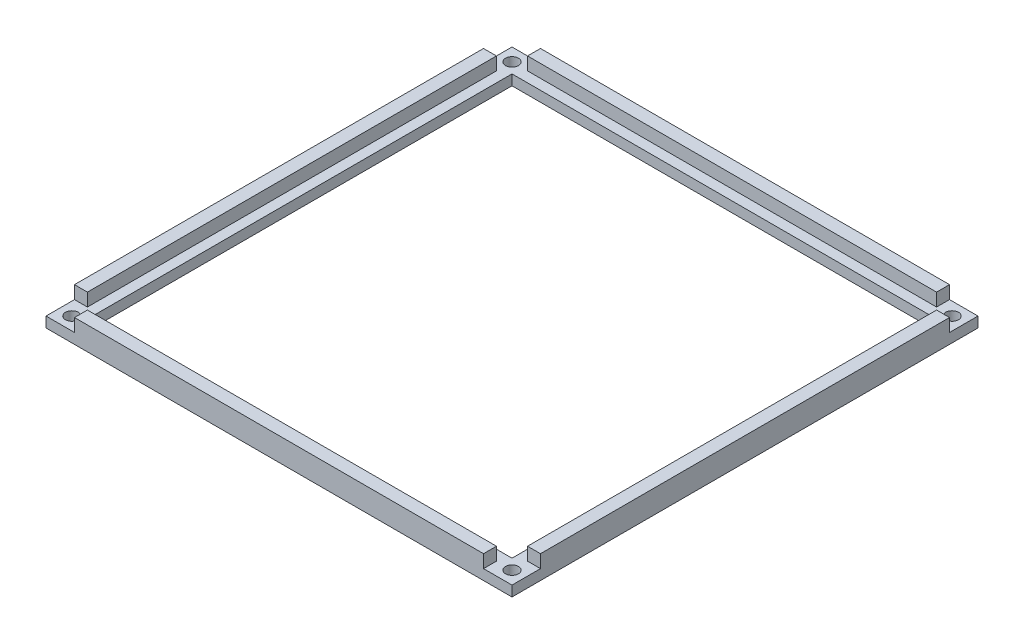
SolidWorks part; units mm, degrees
ref_plane "Alzado" through (0, 0, 0) normal (0, 0, 1) x (1, 0, 0)
ref_plane "Planta" through (0, 0, 0) normal (0, 1, 0) x (1, 0, 0)
ref_plane "Vista lateral" through (0, 0, 0) normal (1, 0, 0) x (0, 0, -1)
sketch "Croquis1" plane through (0, 0, 0) normal (0, 1, 0) x (1, 0, 0)
  line L0 (100, 15) -> (100, 0) construction
  line L1 (0, 0) -> (200, 0)
  line L2 (0, 0) -> (0, 200)
  line L3 (0, 200) -> (200, 200)
  line L4 (200, 0) -> (200, 200)
  line L5 (15, 15) -> (185, 15) construction
  line L6 (15, 15) -> (15, 185) construction
  line L7 (15, 185) -> (185, 185) construction
  line L8 (185, 15) -> (185, 185) construction
  line L9 (185, 100) -> (200, 100) construction
  circle A0 centre (15, 185) radius 2.5
  circle A1 centre (185, 185) radius 2.5
  circle A2 centre (185, 15) radius 2.5
  circle A3 centre (15, 15) radius 2.5
  dimension "D3" = 5
  dimension "D1" = 200
  dimension "D2" = 170
extrude "Saliente-Extruir1" add sketch "Croquis1" along normal blind 4
sketch "Croquis2" plane through (0, 4, 0) normal (0, 1, 0) x (1, 0, 0)
  line L0 (0, 200) -> (200, 0) construction
  line L2 (21, 21) -> (179, 21)
  line L3 (21, 21) -> (21, 179)
  line L4 (21, 179) -> (179, 179)
  line L5 (179, 21) -> (179, 179)
  line L6 (21, 21) -> (179, 179) construction
  line L7 (21, 179) -> (179, 21) construction
  point P4 (100, 100)
  dimension "D1" = 158
extrude "Cortar-Extruir1" cut sketch "Croquis2" against normal blind 10
sketch "Croquis3" plane through (0, 4, 0) normal (0, 1, 0) x (1, 0, 0)
  line L0 (0, 0) -> (200, 0) construction
  line L1 (0, 200) -> (0, 0) construction
  line L2 (200, 200) -> (0, 200) construction
  line L3 (200, 0) -> (200, 200) construction
  line L4 (0, 0) -> (200, 0)
  line L5 (0, 200) -> (0, 0)
  line L6 (200, 200) -> (0, 200)
  line L7 (200, 0) -> (200, 200)
  line L8 (10, 10) -> (190, 10)
  line L9 (190, 10) -> (190, 190)
  line L10 (190, 190) -> (10, 190)
  line L11 (10, 190) -> (10, 10)
  dimension "D1" = 10
extrude "Cortar-Extruir2" cut sketch "Croquis3" against normal blind 10
sketch "Croquis4" plane through (0, 4, 0) normal (0, 1, 0) x (1, 0, 0)
  line L0 (190, 190) -> (10, 190) construction
  line L1 (21, 190) -> (179, 190)
  line L2 (21, 190) -> (21, 185)
  line L3 (21, 185) -> (179, 185)
  line L4 (179, 190) -> (179, 185)
  line L5 (100, 179) -> (100, 185) construction
  line L6 (179, 179) -> (21, 179) construction
  line L7 (21, 100) -> (179, 100) construction
  line L8 (21, 179) -> (21, 21) construction
  line L9 (179, 21) -> (179, 179) construction
  line L10 (100, 179) -> (100, 21) construction
  line L11 (21, 21) -> (179, 21) construction
  line L12 (190, 179) -> (185, 179)
  line L13 (190, 179) -> (190, 21)
  line L14 (190, 21) -> (185, 21)
  line L15 (185, 179) -> (185, 21)
  line L16 (179, 10) -> (179, 15)
  line L17 (179, 10) -> (21, 10)
  line L18 (21, 10) -> (21, 15)
  line L19 (179, 15) -> (21, 15)
  line L20 (10, 21) -> (15, 21)
  line L21 (10, 21) -> (10, 179)
  line L22 (10, 179) -> (15, 179)
  line L23 (15, 21) -> (15, 179)
  dimension "D1" = 5
  dimension "D2" = 158
extrude "Saliente-Extruir2" add sketch "Croquis4" along normal blind 5
sketch "Croquis5" plane through (0, 4, 0) normal (0, 1, 0) x (1, 0, 0)
  line L0 (21, 179) -> (21, 21) construction
  line L1 (21, 21) -> (179, 21) construction
  line L2 (179, 21) -> (179, 179) construction
  line L3 (179, 179) -> (21, 179) construction
  line L4 (21, 179) -> (21, 21)
  line L5 (21, 21) -> (179, 21)
  line L6 (179, 21) -> (179, 179)
  line L7 (179, 179) -> (21, 179)
  line L8 (19, 181) -> (19, 19)
  line L9 (19, 19) -> (181, 19)
  line L10 (181, 19) -> (181, 181)
  line L11 (181, 181) -> (19, 181)
  dimension "D1" = 2
extrude "Cortar-Extruir4" cut sketch "Croquis5" against normal blind 5
